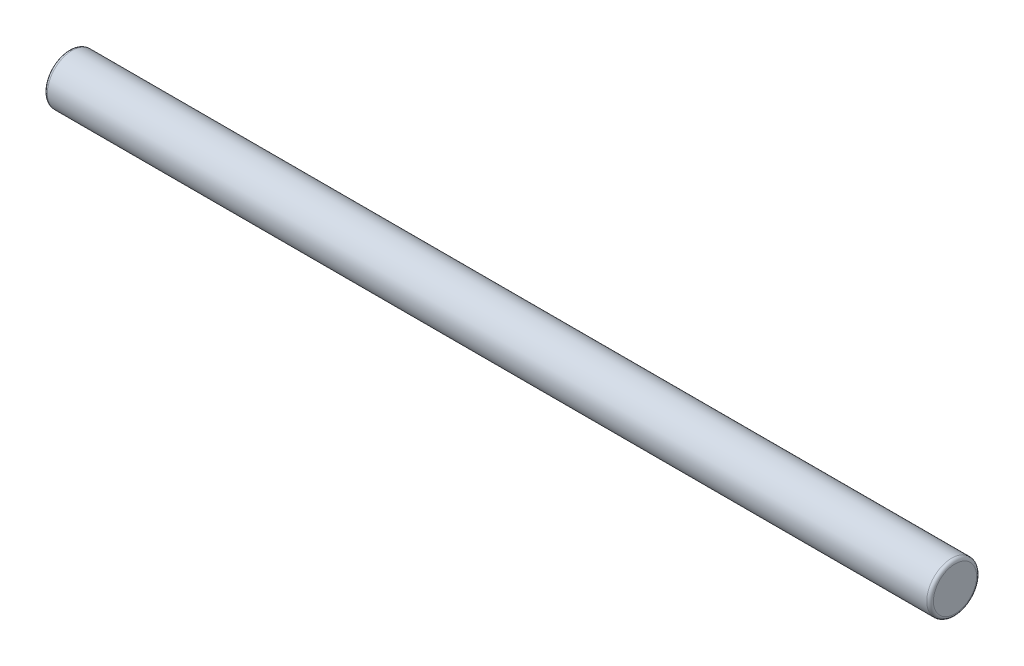
SolidWorks part; units mm, degrees
material "Stainless Steel (ferritic)"
ref_plane "Front Plane" through (0, 0, 0) normal (0, 0, 1) x (1, 0, 0)
ref_plane "Top Plane" through (0, 0, 0) normal (0, 1, 0) x (1, 0, 0)
ref_plane "Right Plane" through (0, 0, 0) normal (1, 0, 0) x (0, 0, -1)
sketch "Sketch1" plane through (0, 0, 0) normal (1, 0, 0) x (0, 0, -1)
  circle A0 centre (0, 0) radius 2.25
  dimension "D1" = 4.5
extrude "Boss-Extrude1" add sketch "Sketch1" along normal mid plane 80
fillet "Fillet1" radius 0.3 2 edges at (-40, 0, -2.25) (40, 0, -2.25)
